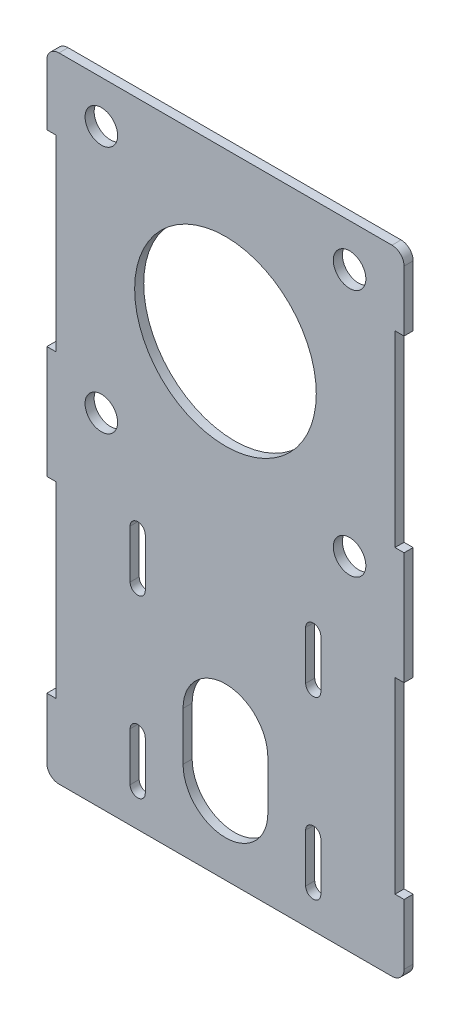
SolidWorks part; units mm, degrees
ref_plane "Front Plane" through (0, 0, 0) normal (0, 0, 1) x (1, 0, 0)
ref_plane "Top Plane" through (0, 0, 0) normal (0, 1, 0) x (1, 0, 0)
ref_plane "Right Plane" through (0, 0, 0) normal (1, 0, 0) x (0, 0, -1)
sketch "Sketch1" plane through (0, 0, 0) normal (0, 0, 1) x (1, 0, 0)
  line L0 (0, 87.3125) -> (0, -244.7446) construction
  line L1 (93.6625, 87.3125) -> (-93.6625, 87.3125)
  line L2 (93.6625, 87.3125) -> (93.6625, -244.7446)
  line L3 (93.6625, -244.7446) -> (-93.6625, -244.7446)
  line L4 (-93.6625, 87.3125) -> (-93.6625, -244.7446)
  line L5 (65.0875, 80.9625) -> (-65.0875, 80.9625) construction
  line L6 (-80.9625, 65.0875) -> (-80.9625, -65.0875) construction
  arc A0 (-47.7494, -219.9794) -> (47.7494, -219.9794) centre (0, -23.368) ccw construction
  point P11 (0, -225.6946)
  dimension "D1" = 6.35
  dimension "D2" = 12.7
  dimension "D3" = 19.05
extrude "Extrude1" add sketch "Sketch1" against normal blind 4.7625
sketch "Sketch2" plane through (0, 0, 0) normal (0, 0, 1) x (1, 0, 0)
  line L0 (22.225, -190.5) -> (-22.225, -190.5) construction
  line L1 (-22.225, -203.2) -> (-22.225, -177.8)
  line L2 (22.225, -203.2) -> (22.225, -177.8)
  line L3 (46.0248, -134.3152) -> (46.0248, -108.9152) construction
  line L4 (-46.0248, -134.3152) -> (-46.0248, -108.9152) construction
  line L5 (-46.0248, -200.9648) -> (-46.0248, -226.3648) construction
  line L6 (46.0248, -200.9648) -> (46.0248, -226.3648) construction
  line L7 (49.9935, -108.9152) -> (49.9935, -134.3152)
  line L8 (42.0561, -108.9152) -> (42.0561, -134.3152)
  line L9 (-42.056, -108.9152) -> (-42.056, -134.3152)
  line L10 (-49.9935, -108.9152) -> (-49.9935, -134.3152)
  line L11 (49.9935, -200.9648) -> (49.9935, -226.3648)
  line L12 (42.0561, -226.3648) -> (42.056, -200.9648)
  line L13 (-42.0561, -200.9648) -> (-42.0561, -226.3648)
  line L14 (-49.9936, -200.9648) -> (-49.9935, -226.3648)
  arc A0 (2.3812, -199.7225) -> (-2.3813, -199.7225) centre (0, -190.5) ccw construction
  arc A1 (22.225, -177.8) -> (-22.225, -177.8) centre (0, -177.8) ccw
  arc A2 (-22.225, -203.2) -> (22.225, -203.2) centre (0, -203.2) ccw
  arc A3 (49.9935, -108.9152) -> (42.0561, -108.9152) centre (46.0248, -108.9152) ccw
  arc A4 (42.0561, -134.3152) -> (49.9935, -134.3152) centre (46.0248, -134.3152) ccw
  arc A5 (-49.9935, -134.3152) -> (-42.056, -134.3152) centre (-46.0248, -134.3152) ccw
  arc A6 (-42.056, -108.9152) -> (-49.9935, -108.9152) centre (-46.0248, -108.9152) ccw
  arc A7 (-42.0561, -200.9648) -> (-49.9936, -200.9648) centre (-46.0248, -200.9648) ccw
  arc A8 (-49.9935, -226.3648) -> (-42.0561, -226.3648) centre (-46.0248, -226.3648) ccw
  arc A9 (49.9935, -200.9648) -> (42.056, -200.9648) centre (46.0248, -200.9648) ccw
  arc A10 (49.9935, -226.3648) -> (42.0561, -226.3648) centre (46.0248, -226.3648) cw
  point P0 (0, -190.5)
  point P12 (46.0248, -121.6152)
  point P16 (-46.0248, -121.6152)
  point P20 (-46.0248, -213.6648)
  point P21 (46.0248, -213.6648)
  dimension "D3" = 7.9375
  dimension "D1" = 25.4
  dimension "D2" = 44.45
extrude "Cut-Extrude1" cut sketch "Sketch2" against normal up to next
sketch "Sketch3" plane through (0, 0, 0) normal (0, 0, -1) x (-1, 0, 0)
  circle A0 centre (0, 0) radius 47.625
  circle A1 centre (65.0875, 65.0875) radius 8.5328
  circle A2 centre (-65.0875, 65.0875) radius 8.5328
  circle A3 centre (-65.0875, -65.0875) radius 8.5328
  circle A4 centre (65.0875, -65.0875) radius 8.5328
  circle A5 centre (65.0875, -65.0875) radius 8.5328 construction
  circle A6 centre (65.0875, 65.0875) radius 8.5328 construction
  circle A7 centre (-65.0875, 65.0875) radius 8.5328 construction
  circle A8 centre (-65.0875, -65.0875) radius 8.5328 construction
  dimension "D1" = 95.25
extrude "Cut-Extrude2" cut sketch "Sketch3" along normal up to next
fillet "Fillet1" radius 6.35 4 edges at (-93.6625, 87.3125, -2.3813) (-93.6625, -244.7446, -2.3813) (93.6625, -244.7446, -2.3813) (93.6625, 87.3125, -2.3813)
sketch "Sketch4" plane through (0, 0, -4.7625) normal (0, 0, -1) x (-1, 0, 0)
  line L1 (-93.6625, 49.2125) -> (-88.9, 49.2125)
  line L2 (-93.6625, 49.2125) -> (-93.6625, -49.2125)
  line L3 (-93.6625, -49.2125) -> (-88.9, -49.2125)
  line L4 (-88.9, 49.2125) -> (-88.9, -49.2125)
  line L5 (-93.6625, -108.2196) -> (-88.9, -108.2196)
  line L6 (-93.6625, -108.2196) -> (-93.6625, -206.6446)
  line L7 (-93.6625, -206.6446) -> (-88.9, -206.6446)
  line L8 (-88.9, -108.2196) -> (-88.9, -206.6446)
  line L9 (-93.6625, -78.716) -> (93.6625, -78.716) construction
  line L10 (-93.6625, -238.3946) -> (-93.6625, 80.9625) construction
  line L11 (93.6625, 80.9625) -> (93.6625, -238.3946) construction
  line L12 (-87.3125, 87.3125) -> (87.3125, 87.3125) construction
  line L13 (0, 0) -> (-93.6625, 0) construction
  dimension "D1" = 38.1
  dimension "D2" = 4.7625
extrude "Cut-Extrude3" cut sketch "Sketch4" against normal up to next
mirror "Mirror1" about plane through (0, 0, 0) normal (1, 0, 0) of "Cut-Extrude3"
